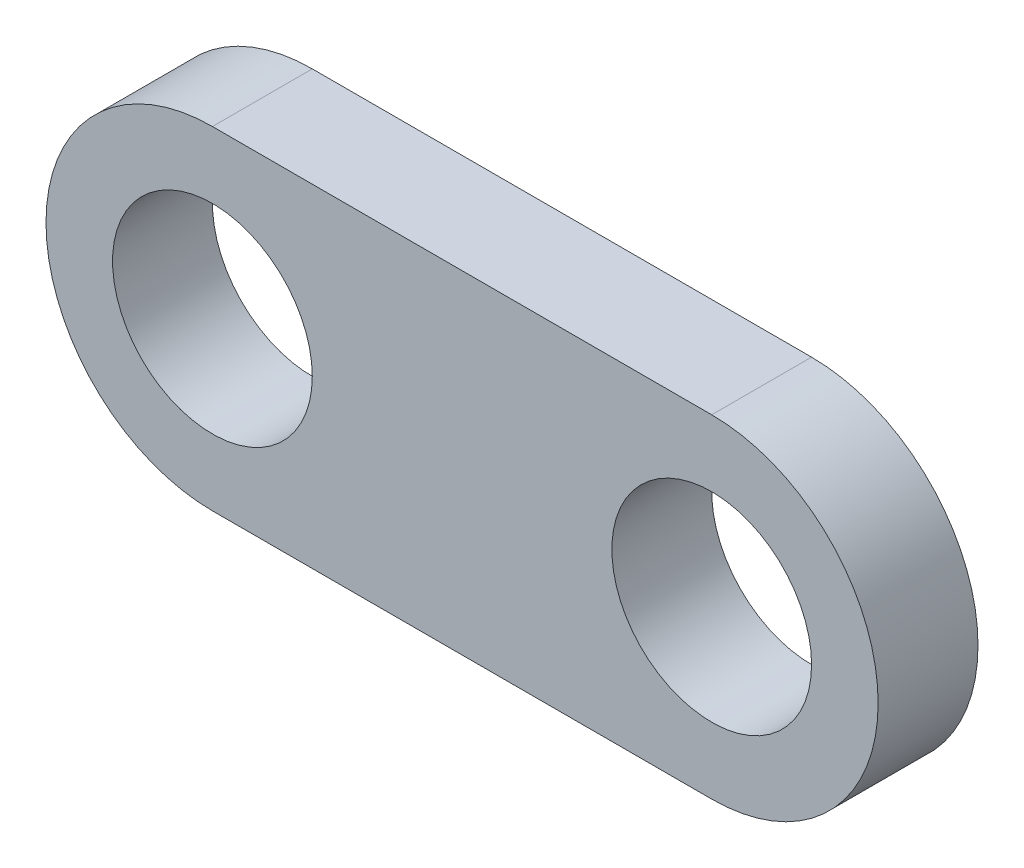
SolidWorks part; units mm, degrees
ref_plane "正面" through (0, 0, 0) normal (0, 0, 1) x (1, 0, 0)
ref_plane "平面" through (0, 0, 0) normal (0, 1, 0) x (1, 0, 0)
ref_plane "右側面" through (0, 0, 0) normal (1, 0, 0) x (0, 0, -1)
sketch "ｽｹｯﾁ1" plane through (0, 0, 0) normal (0, 0, 1) x (1, 0, 0)
  line L0 (-7.5, 0) -> (7.5, 0) construction
  line L1 (-7.5, 5) -> (7.5, 5)
  line L2 (-7.5, -5) -> (7.5, -5)
  arc A0 (-7.5, 5) -> (-7.5, -5) centre (-7.5, 0) ccw
  arc A1 (7.5, -5) -> (7.5, 5) centre (7.5, 0) ccw
  circle A2 centre (-7.5, 0) radius 3
  circle A3 centre (7.5, 0) radius 3
  point P2 (0, 0)
  dimension "D1" = 6
  dimension "D2" = 5
  dimension "D3" = 15
extrude "ﾎﾞｽ - 押し出し1" add sketch "ｽｹｯﾁ1" along normal blind 3
